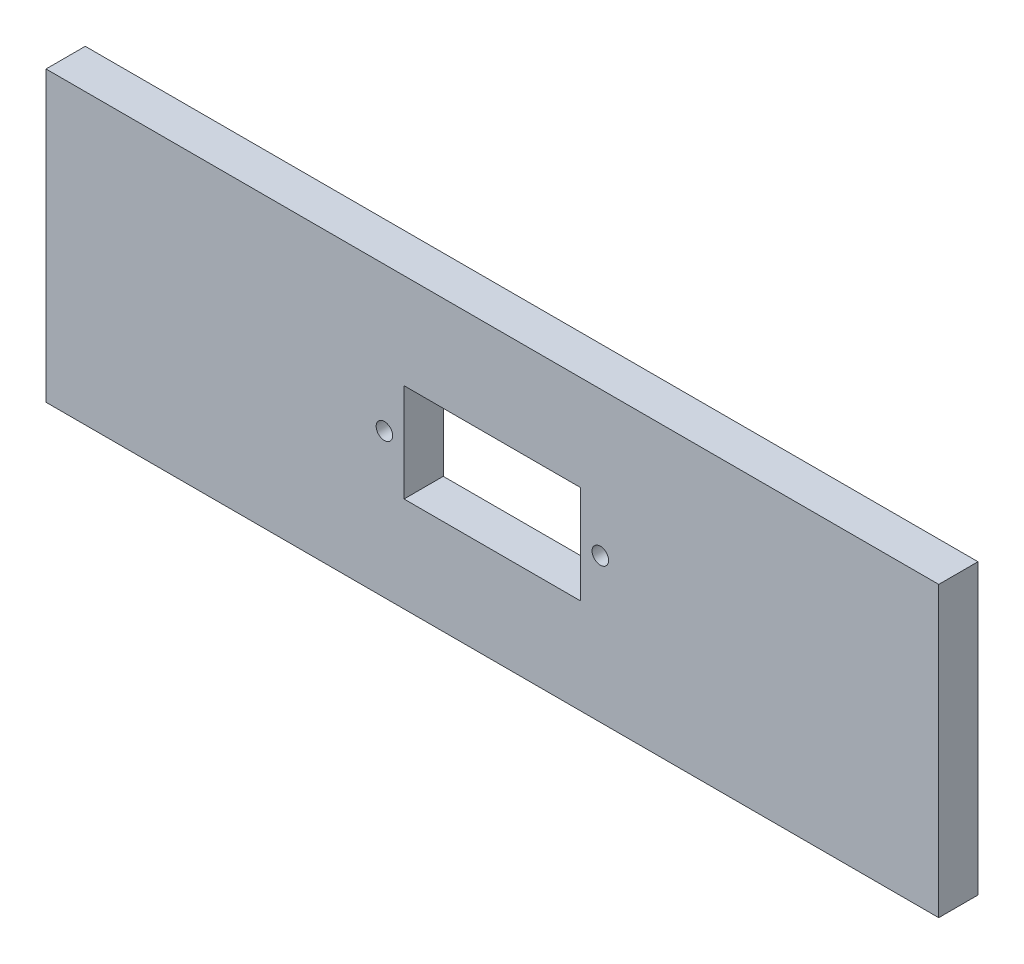
SolidWorks part; units mm, degrees
material "ﾁｰｸ材"
ref_plane "正面" through (0, 0, 0) normal (0, 0, 1) x (1, 0, 0)
ref_plane "平面" through (0, 0, 0) normal (0, 1, 0) x (1, 0, 0)
ref_plane "右側面" through (0, 0, 0) normal (1, 0, 0) x (0, 0, -1)
sketch "ｽｹｯﾁ1" plane through (0, 0, 0) normal (0, 0, 1) x (1, 0, 0)
  line L1 (-56.8441, 18.3807) -> (56.8441, 18.3807)
  line L2 (-56.8441, 18.3807) -> (-56.8441, -18.3807)
  line L3 (-56.8441, -18.3807) -> (56.8441, -18.3807)
  line L4 (56.8441, 18.3807) -> (56.8441, -18.3807)
  line L5 (-56.8441, 18.3807) -> (56.8441, -18.3807) construction
  line L6 (-56.8441, -18.3807) -> (56.8441, 18.3807) construction
  line L7 (11.25, 6.25) -> (-11.25, 6.25)
  line L8 (11.25, 6.25) -> (11.25, -6.25)
  line L9 (11.25, -6.25) -> (-11.25, -6.25)
  line L10 (-11.25, 6.25) -> (-11.25, -6.25)
  line L11 (11.25, 6.25) -> (-11.25, -6.25) construction
  line L12 (11.25, -6.25) -> (-11.25, 6.25) construction
  circle A0 centre (-13.75, 0) radius 1.05
  circle A1 centre (13.75, 0) radius 1.05
  point P0 (0, 0)
  point P6 (0, 0)
  dimension "D3" = 2.1
  dimension "D4" = 2.1
  dimension "D1" = 12.5
  dimension "D2" = 22.5
  dimension "D5" = 2.5
  dimension "D6" = 2.5
extrude "ﾎﾞｽ - 押し出し1" add sketch "ｽｹｯﾁ1" along normal blind 5
